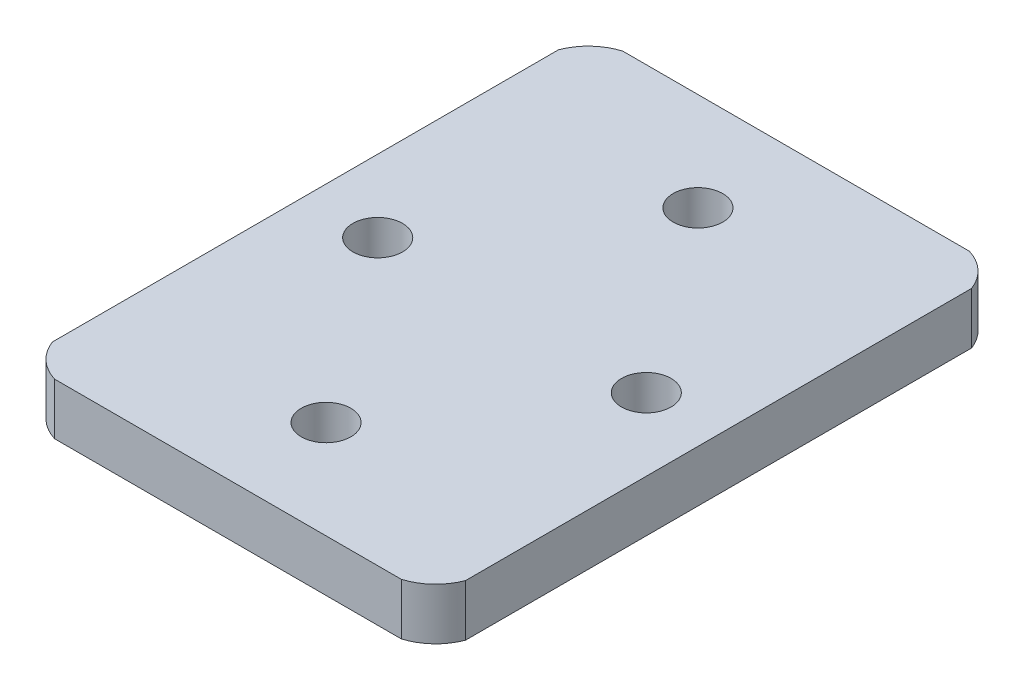
SolidWorks part; units mm, degrees
ref_plane "Front Plane" through (0, 0, 0) normal (0, 0, 1) x (1, 0, 0)
ref_plane "Top Plane" through (0, 0, 0) normal (0, 1, 0) x (1, 0, 0)
ref_plane "Right Plane" through (0, 0, 0) normal (1, 0, 0) x (0, 0, -1)
sketch "Sketch1" plane through (0, 0, 0) normal (0, 1, 0) x (1, 0, 0)
  line L0 (0, 48.3783) -> (0, -25.7733) construction
  line L1 (-16.782, 33.0126) -> (16.782, 33.0126)
  line L2 (20, 30.0126) -> (20, -18.9874)
  line L3 (16.782, -21.9874) -> (-16.782, -21.9874)
  line L4 (-20, 30.0126) -> (-20, -18.9874)
  line L5 (-20, 5.5126) -> (20, 5.5126) construction
  circle A4 centre (0, 23.5126) radius 2.4
  circle A5 centre (-13, 5.5126) radius 2.4
  circle A6 centre (0, -12.4874) radius 2.4
  circle A7 centre (13, 5.5126) radius 2.4
  arc A8 (-16.782, 33.0126) -> (-20, 30.0126) centre (-15.3292, 28.2284) ccw
  arc A9 (16.782, 33.0126) -> (20, 30.0126) centre (15.3292, 28.2284) cw
  arc A10 (16.782, -21.9874) -> (20, -18.9874) centre (15.3292, -17.2031) ccw
  arc A11 (-16.782, -21.9874) -> (-20, -18.9874) centre (-15.3292, -17.2031) cw
  point P12 (0, -21.9874)
  point P17 (0, 33.0126)
  dimension "D4" = 4.8
  dimension "D6" = 26
  dimension "D1" = 40
  dimension "D2" = 55
  dimension "D5" = 36
extrude "Boss-Extrude1" add sketch "Sketch1" along normal blind 5
